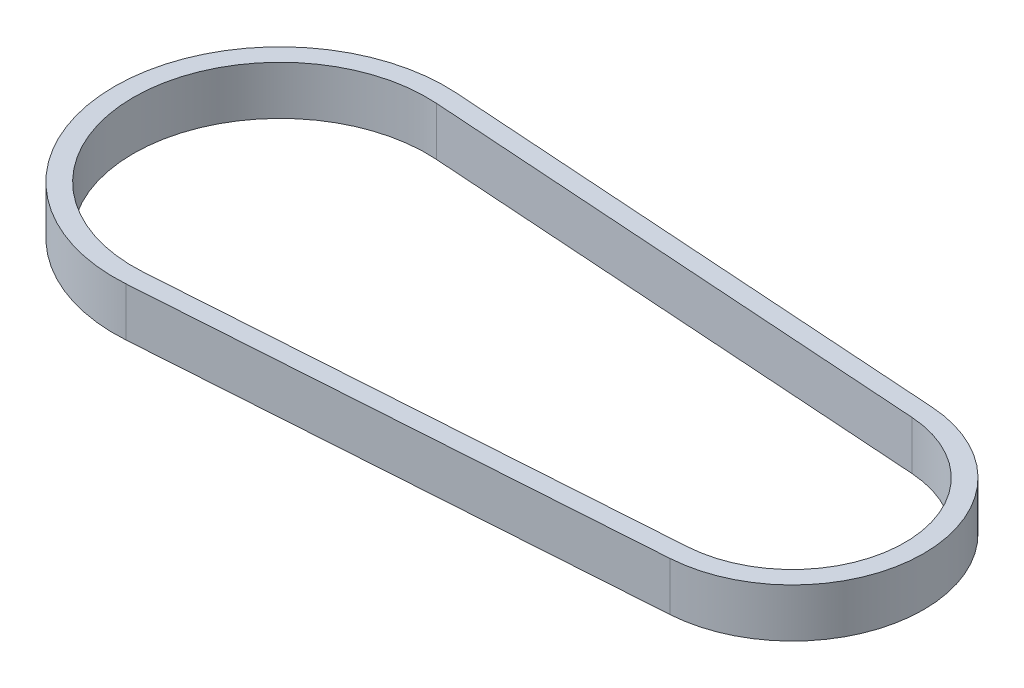
SolidWorks part; units mm, degrees
material "Rubber"
ref_plane "Front Plane" through (0, 0, 0) normal (0, 0, 1) x (1, 0, 0)
ref_plane "Top Plane" through (0, 0, 0) normal (0, 1, 0) x (1, 0, 0)
ref_plane "Right Plane" through (0, 0, 0) normal (1, 0, 0) x (0, 0, -1)
sketch "Sketch1" plane through (0, 0, 0) normal (0, 1, 0) x (1, 0, 0)
  line L0 (1.9191, -28.5857) -> (96.2937, -22.2499)
  line L1 (1.9191, 28.5857) -> (96.2937, 22.2499)
  line L2 (2.053, 30.5812) -> (96.4277, 24.2454)
  line L3 (2.053, -30.5812) -> (96.4277, -24.2454)
  line L4 (1.8186, 27.089) -> (96.1932, 20.7533)
  line L5 (1.8186, -27.089) -> (96.1932, -20.7533)
  arc A0 (1.9191, 28.5857) -> (1.9191, -28.5857) centre (0, 0) ccw
  arc A1 (96.2937, -22.2499) -> (96.2937, 22.2499) centre (94.8, 0) ccw
  arc A2 (96.4277, -24.2454) -> (96.4277, 24.2454) centre (94.8, 0) ccw
  arc A3 (2.053, 30.5812) -> (2.053, -30.5812) centre (0, 0) ccw
  arc A4 (96.1932, -20.7533) -> (96.1932, 20.7533) centre (94.8, 0) ccw
  arc A5 (1.8186, 27.089) -> (1.8186, -27.089) centre (0, 0) ccw
  dimension "D1" = 57.3
  dimension "D2" = 44.6
  dimension "D3" = 94.8
  dimension "D4" = 2
  dimension "D5" = 1.5
extrude "Boss-Extrude1" add sketch "Sketch1" along normal blind 9 contours L0 A1 L1 A0 A5 L4 A4 L5 | L2 A3 L3 A2 A1 L0 A0 L1
